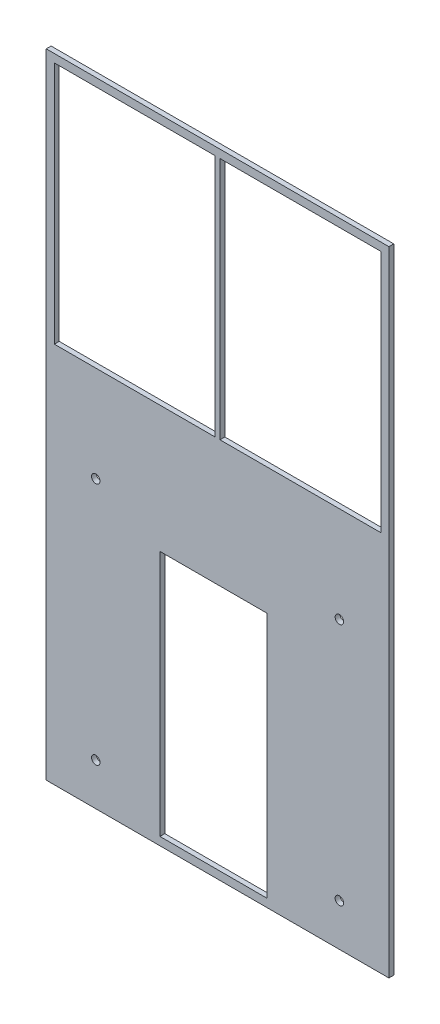
SolidWorks part; units mm, degrees
ref_plane "Front Plane" through (0, 0, 0) normal (0, 0, 1) x (1, 0, 0)
ref_plane "Top Plane" through (0, 0, 0) normal (0, 1, 0) x (1, 0, 0)
ref_plane "Right Plane" through (0, 0, 0) normal (1, 0, 0) x (0, 0, -1)
sketch "Sketch1" plane through (0, 0, 0) normal (0, 0, 1) x (1, 0, 0)
  line L0 (-49.5, 0) -> (49.5, 0) construction
  line L1 (-49.5, 75) -> (49.5, 75)
  line L2 (-49.5, 75) -> (-49.5, -75)
  line L3 (-49.5, -75) -> (49.5, -75)
  line L4 (49.5, 75) -> (49.5, -75)
  line L5 (52.5, 75) -> (151.5, 75)
  line L6 (52.5, 75) -> (52.5, -75)
  line L7 (52.5, -75) -> (151.5, -75)
  line L8 (151.5, 75) -> (151.5, -75)
  line L9 (15.5, -153) -> (81.5, -153)
  line L10 (15.5, -153) -> (15.5, -305)
  line L11 (15.5, -305) -> (81.5, -305)
  line L12 (81.5, -153) -> (81.5, -305)
  line L13 (-54.5, 80) -> (156.5, 80)
  line L14 (-54.5, 80) -> (-54.5, -310)
  line L15 (-54.5, -310) -> (156.5, -310)
  line L16 (156.5, 80) -> (156.5, -310)
  line L17 (0, 75) -> (0, -75) construction
  point P20 (0, 0)
  dimension "D1" = 99
  dimension "D2" = 150
  dimension "D3" = 5
  dimension "D4" = 5
  dimension "D5" = 5
  dimension "D6" = 3
  dimension "D7" = 5
  dimension "D8" = 390
  dimension "D9" = 5
  dimension "D10" = 66
  dimension "D11" = 152
  dimension "D12" = 70
extrude "Boss-Extrude1" add sketch "Sketch1" along normal blind 3
sketch "Sketch2" plane through (0, 0, 3) normal (0, 0, 1) x (1, 0, 0)
  line L0 (-24, -134) -> (126, -134) construction
  line L2 (-54.5, -310) -> (156.5, -310) construction
  circle A0 centre (-24, -134) radius 2.6
  circle A1 centre (126, -134) radius 2.6
  circle A2 centre (126, -284) radius 2.6
  circle A3 centre (-24, -284) radius 2.6
  point P10 (51, -310)
  point P11 (51, -134)
  dimension "D1" = 5.2
  dimension "D2" = 150
  dimension "D3" = 150
  dimension "D4" = 26
extrude "Cut-Extrude1" cut sketch "Sketch2" against normal through all
